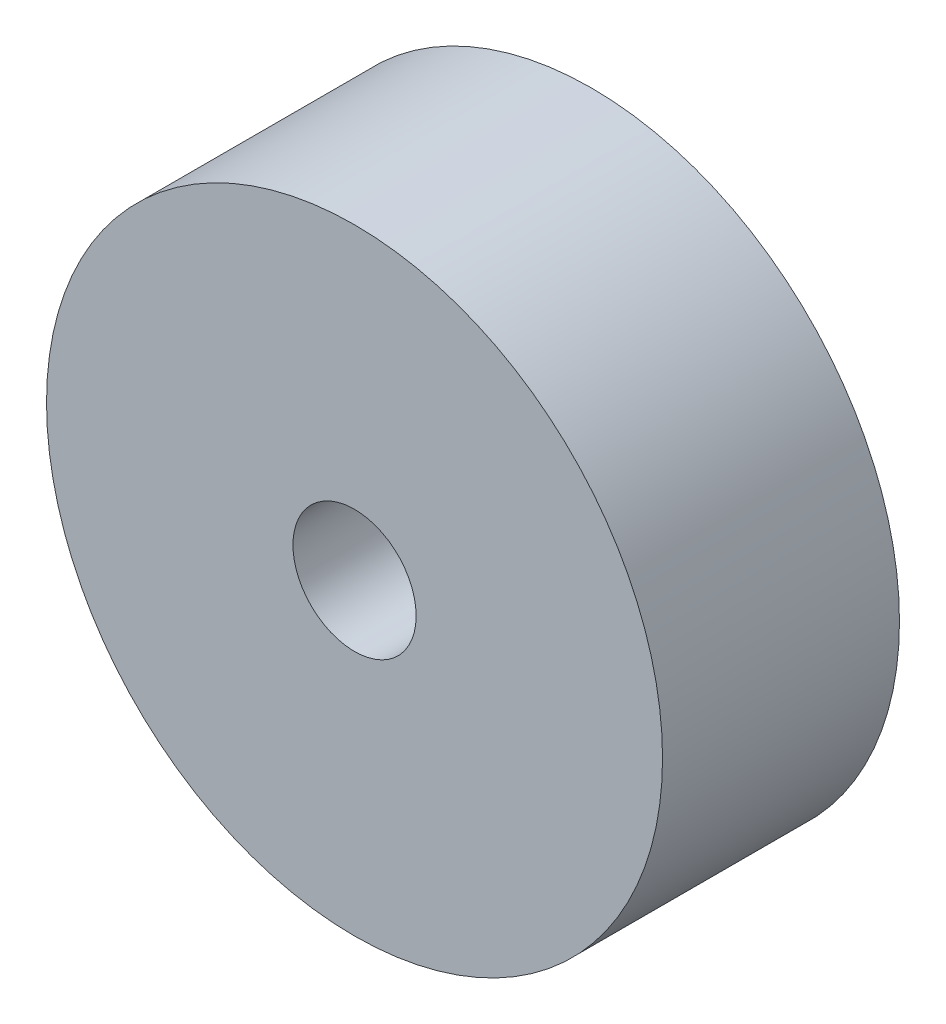
SolidWorks part; units mm, degrees
material "ABS PC"
ref_plane "Front Plane" through (0, 0, 0) normal (0, 0, 1) x (1, 0, 0)
ref_plane "Top Plane" through (0, 0, 0) normal (0, 1, 0) x (1, 0, 0)
ref_plane "Right Plane" through (0, 0, 0) normal (1, 0, 0) x (0, 0, -1)
sketch "Sketch1" plane through (0, 0, 0) normal (0, 0, 1) x (1, 0, 0)
  circle A0 centre (0, 0) radius 6.5
  circle A1 centre (0, 0) radius 1.3
  dimension "D1" = 13
  dimension "D2" = 2.6
extrude "Boss-Extrude5" add sketch "Sketch1" along normal blind 5
